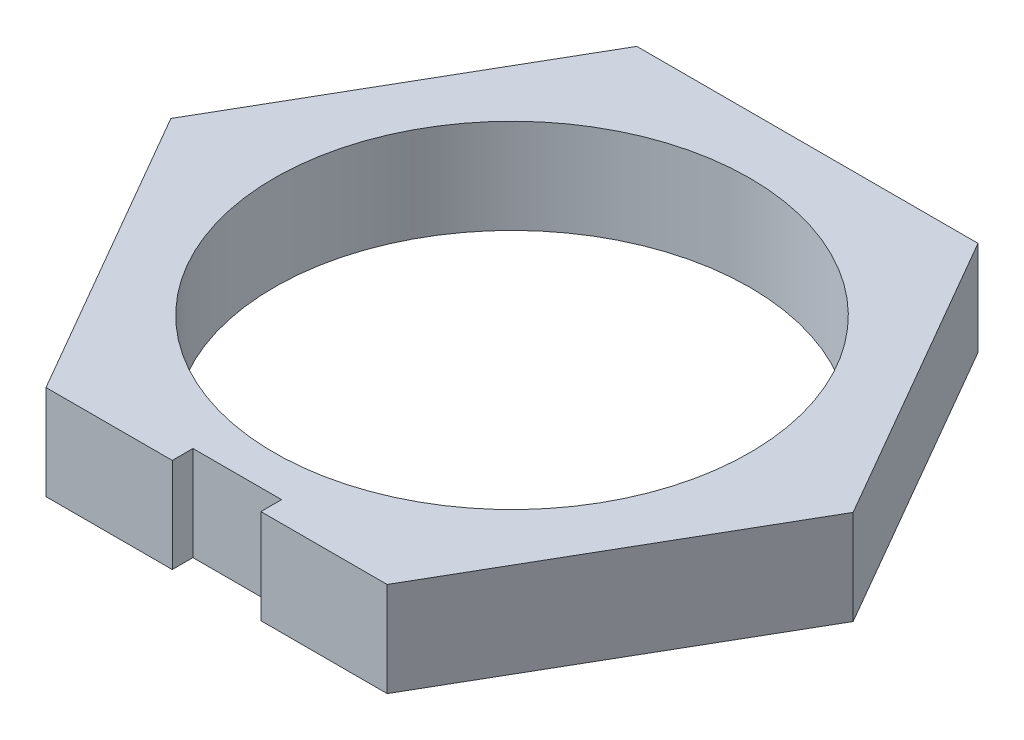
SolidWorks part; units mm, degrees
ref_plane "Front Plane" through (0, 0, 0) normal (0, 0, 1) x (1, 0, 0)
ref_plane "Top Plane" through (0, 0, 0) normal (0, 1, 0) x (1, 0, 0)
ref_plane "Right Plane" through (0, 0, 0) normal (1, 0, 0) x (0, 0, -1)
ref_plane "Plane1" through (0, 2.032, 0) normal (0, 1, 0) x (-1, 0, 0)
sketch "Sketch1" plane through (0, 2.032, 0) normal (0, 1, 0) x (-1, 0, 0)
  line L0 (1.905, 12.7) -> (1.905, 11.811)
  line L1 (1.905, 11.811) -> (-1.905, 11.811)
  line L2 (-1.905, 11.811) -> (-1.905, 12.7)
  line L3 (-1.905, 12.7) -> (-7.3323, 12.7)
  line L4 (-7.3323, 12.7) -> (-14.6647, 0)
  line L5 (-14.6647, 0) -> (-7.3323, -12.7)
  line L6 (-7.3323, -12.7) -> (7.3323, -12.7)
  line L7 (7.3323, -12.7) -> (14.6647, 0)
  line L8 (14.6647, 0) -> (7.3323, 12.7)
  line L9 (7.3323, 12.7) -> (1.905, 12.7)
  circle A0 centre (0, 0) radius 10.2235
extrude "Boss-Extrude1" add sketch "Sketch1" against normal blind 4.064
